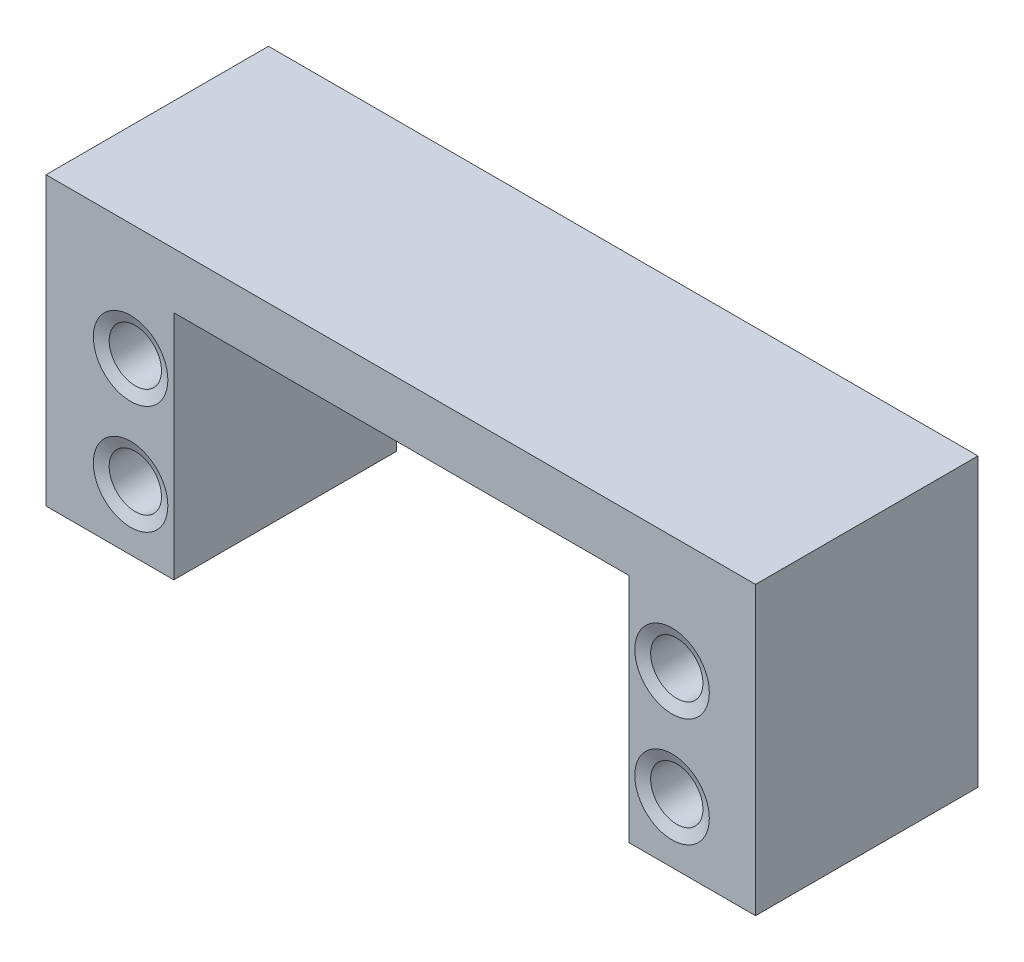
SolidWorks part; units mm, degrees
ref_plane "Front Plane" through (0, 0, 0) normal (0, 0, 1) x (1, 0, 0)
ref_plane "Top Plane" through (0, 0, 0) normal (0, 1, 0) x (1, 0, 0)
ref_plane "Right Plane" through (0, 0, 0) normal (1, 0, 0) x (0, 0, -1)
sketch "Sketch1" plane through (0, 0, 0) normal (0, 0, 1) x (1, 0, 0)
  line L1 (-48.395, 10.4) -> (48.395, 10.4) construction
  line L2 (-48.395, 10.4) -> (-48.395, -10.4) construction
  line L3 (-48.395, -10.4) -> (48.395, -10.4) construction
  line L4 (48.395, 10.4) -> (48.395, -10.4) construction
  line L5 (-48.395, 10.4) -> (48.395, -10.4) construction
  line L6 (-48.395, -10.4) -> (48.395, 10.4) construction
  line L7 (-48.395, -10.4) -> (-29.9, -10.4)
  line L8 (-48.395, -10.4) -> (-48.395, 10.4)
  line L9 (-48.395, 10.4) -> (-29.9, 10.4)
  line L10 (-29.9, -10.4) -> (-29.9, 10.4)
  line L11 (-48.395, -10.4) -> (-29.9, 10.4) construction
  line L12 (-48.395, 10.4) -> (-29.9, -10.4) construction
  line L13 (48.395, 10.4) -> (11, 10.4)
  line L14 (48.395, 10.4) -> (48.395, -10.4)
  line L15 (48.395, -10.4) -> (11, -10.4)
  line L16 (11, 10.4) -> (11, -10.4)
  line L17 (48.395, 10.4) -> (11, -10.4) construction
  line L18 (48.395, -10.4) -> (11, 10.4) construction
  line L19 (-48.395, 10.4) -> (-58.395, 10.4)
  line L20 (-48.395, 10.4) -> (-48.395, -10.4)
  line L21 (-48.395, -10.4) -> (-58.395, -10.4)
  line L22 (-58.395, 10.4) -> (-58.395, -10.4)
  line L23 (-48.395, 10.4) -> (-58.395, -10.4) construction
  line L24 (-48.395, -10.4) -> (-58.395, 10.4) construction
  point P0 (0, 0)
  point P8 (-39.1475, 0)
  point P11 (29.6975, 0)
  point P14 (-53.395, 0)
  dimension "D1" = 96.79
  dimension "D2" = 20.8
  dimension "D3" = 18.495
  dimension "D4" = 37.395
  dimension "D5" = 10
extrude "Boss-Extrude1" add sketch "Sketch1" along normal blind 20 contours L2 L1 L4 L3 | L8 L7 L10 L9 | L14 L13 L16 L15 | L20 L19 L22 L21
sketch "Sketch6" plane through (0, 10.4, 0) normal (0, 1, 0) x (1, 0, 0)
  line L5 (48.395, -20) -> (48.395, 0) construction
  line L6 (-58.395, 0) -> (48.395, 0)
  line L7 (-58.395, 0) -> (-58.395, -20)
  line L8 (-58.395, -20) -> (48.395, -20)
  line L9 (48.395, 0) -> (48.395, -20)
  line L10 (-58.395, 0) -> (48.395, -20) construction
  line L11 (-58.395, -20) -> (48.395, 0) construction
  point P4 (-5, -10)
  dimension "D1" = 20
extrude "Boss-Extrude4" add sketch "Sketch6" along normal blind 5
sketch "Sketch9" plane through (0, 0, 20) normal (0, 0, 1) x (1, 0, 0)
  line L0 (11, 10.4) -> (-29.9, 10.4) construction
  line L1 (-9.45, 10.4) -> (-9.45, -6.4957) construction
  line L2 (11, 10.4) -> (11, -10.4) construction
  line L3 (11, 0) -> (14.89, 0) construction
  line L4 (14.89, 0) -> (14.89, -4.9) construction
  circle A0 centre (14.89, -4.9) radius 2.35
  circle A1 centre (14.89, 4.9) radius 2.35
  circle A2 centre (-33.79, -4.9) radius 2.35
  circle A3 centre (-33.79, 4.9) radius 2.35
  dimension "D3" = 4.7
  dimension "D1" = 3.89
  dimension "D2" = 4.9
extrude "Cut-Extrude1" cut sketch "Sketch9" against normal blind 10
sketch "Sketch10" plane through (-58.395, 0, 0) normal (-1, 0, 0) x (0, 0, 1)
  line L4 (0, 15.4) -> (0, -10.4)
  line L5 (0, -10.4) -> (20, -10.4)
  line L6 (20, -10.4) -> (20, 15.4)
  line L7 (20, 15.4) -> (0, 15.4)
  line L8 (0, 15.4) -> (0, -10.4)
  line L9 (0, -10.4) -> (20, -10.4)
  line L10 (20, -10.4) -> (20, 15.4)
  line L11 (20, 15.4) -> (0, 15.4)
  dimension "D1" = 0
extrude "Cut-Extrude2" cut sketch "Sketch10" against normal blind 17
sketch "Sketch11" plane through (48.395, 0, 0) normal (1, 0, 0) x (0, 0, -1)
  line L4 (-20, 15.4) -> (-20, -10.4)
  line L5 (-20, -10.4) -> (0, -10.4)
  line L6 (0, -10.4) -> (0, 15.4)
  line L7 (0, 15.4) -> (-20, 15.4)
  line L9 (-20, -10.4) -> (0, -10.4)
  line L10 (0, -10.4) -> (0, 15.4)
  line L11 (0, 15.4) -> (-20, 15.4)
  line L12 (-20, 15.4) -> (-20, -10.4)
  dimension "D1" = 0
extrude "Cut-Extrude3" cut sketch "Sketch11" against normal blind 26
chamfer "Chamfer1" distance 1 angle 23 4 edges at (17.24, -4.9, 20) (12.54, 4.9, 20) (-31.44, 4.9, 20) (-36.14, -4.9, 20)
